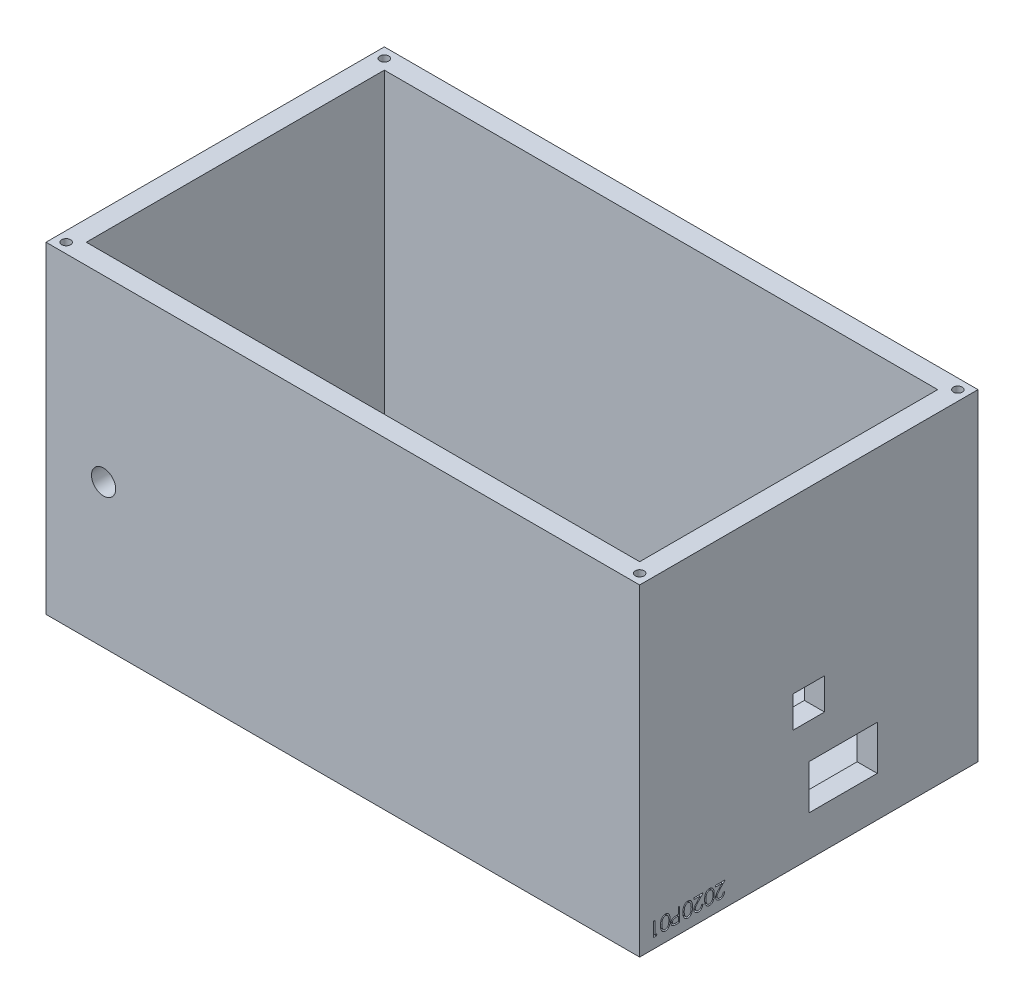
SolidWorks part; units mm, degrees
ref_plane "Front Plane" through (0, 0, 0) normal (0, 0, 1) x (1, 0, 0)
ref_plane "Top Plane" through (0, 0, 0) normal (0, 1, 0) x (1, 0, 0)
ref_plane "Right Plane" through (0, 0, 0) normal (1, 0, 0) x (0, 0, -1)
sketch "Sketch1" plane through (0, 0, 0) normal (0, 1, 0) x (1, 0, 0)
  line L0 (0, 0) -> (-147.35, 0)
  line L1 (-147.35, 0) -> (-147.35, 83.98)
  line L2 (-147.35, 83.98) -> (0, 83.98)
  line L3 (0, 83.98) -> (0, 0)
  dimension "D1" = 147.35
  dimension "D2" = 83.98
extrude "platform_thickness" add sketch "Sketch1" along normal blind 5
sketch "Sketch2" plane through (0, 5, 0) normal (0, 1, 0) x (1, 0, 0)
  line L0 (-147.35, 83.98) -> (-147.35, 0)
  line L1 (-147.35, 0) -> (0, 0)
  line L2 (0, 0) -> (0, 83.98)
  line L3 (0, 83.98) -> (-147.35, 83.98)
  line L4 (-142.35, 78.98) -> (-142.35, 5)
  line L5 (-142.35, 5) -> (-5, 5)
  line L6 (-5, 5) -> (-5, 78.98)
  line L7 (-5, 78.98) -> (-142.35, 78.98)
  line L8 (-5, 5) -> (-5, 0) construction
  line L9 (-5, 5) -> (0, 5) construction
  line L10 (-142.35, 5) -> (-147.35, 5) construction
  line L11 (-142.35, 78.98) -> (-142.35, 83.98) construction
  dimension "D1" = 5
  dimension "D2" = 5
extrude "side_thickness" add sketch "Sketch2" along normal blind 75
sketch "Sketch5" plane through (0, 80, 0) normal (0, 1, 0) x (1, 0, 0)
  line L0 (-2.5, 2.5) -> (-2.5, 81.48) construction
  line L1 (-2.5, 81.48) -> (-144.85, 81.48) construction
  line L2 (-144.85, 81.48) -> (-144.85, 2.5) construction
  line L3 (-144.85, 2.5) -> (-2.5, 2.5) construction
  line L4 (-144.85, 2.5) -> (-144.85, 0) construction
  line L5 (-147.35, 0) -> (0, 0) construction
  line L6 (-144.85, 81.48) -> (-144.85, 83.98) construction
  line L7 (0, 83.98) -> (-147.35, 83.98) construction
  line L8 (-2.5, 2.5) -> (-2.5, 0) construction
  line L9 (-2.5, 81.48) -> (-2.5, 83.98) construction
  line L10 (-144.85, 2.5) -> (-147.35, 2.5) construction
  line L11 (-147.35, 83.98) -> (-147.35, 0) construction
  line L12 (-144.85, 81.48) -> (-147.35, 81.48) construction
  line L13 (-2.5, 81.48) -> (0, 81.48) construction
  line L14 (0, 0) -> (0, 83.98) construction
  line L15 (-2.5, 2.5) -> (0, 2.5) construction
  circle A0 centre (-144.85, 2.5) radius 1.1
  circle A1 centre (-144.85, 81.48) radius 1.1
  circle A2 centre (-2.5, 81.48) radius 1.1
  circle A3 centre (-2.5, 2.5) radius 1.1
  dimension "D1" = 2.2
  dimension "D2" = 2.5
extrude "mounting_holes_1" cut sketch "Sketch5" against normal blind 5
sketch "Sketch11" plane through (0, 0, 0) normal (0, 0, 1) x (1, 0, 0)
  line L0 (-147.35, 0) -> (0, 0) construction
  line L1 (-147.35, 80) -> (-147.35, 0) construction
  circle A0 centre (-133.06, 35.59) radius 3
  point P6 (-147.35, 35.1186)
  point P9 (-126.9793, 33.4193)
  dimension "D1" = 6
  dimension "D2" = 35.59
  dimension "D3" = 14.29
extrude "io_hole_3" cut sketch "Sketch11" against normal blind 50
sketch "Sketch6" plane through (0, 0, 0) normal (1, 0, 0) x (0, 0, -1)
  line L0 (38.09, 37.54) -> (45.89, 37.54)
  line L1 (45.89, 37.54) -> (45.89, 29.74)
  line L2 (45.89, 29.74) -> (38.09, 29.74)
  line L3 (38.09, 29.74) -> (38.09, 37.54)
  line L4 (45.89, 37.54) -> (83.98, 37.54) construction
  line L5 (83.98, 80) -> (83.98, 0) construction
  line L6 (38.09, 37.54) -> (0, 37.54) construction
  line L7 (0, 80) -> (0, 0) construction
  line L8 (38.09, 29.74) -> (38.09, 0) construction
  line L9 (0, 0) -> (83.98, 0) construction
  dimension "D1" = 7.8
  dimension "D3" = 7.8
  dimension "D4" = 29.74
extrude "io_hole_1" cut sketch "Sketch6" against normal blind 92
sketch "Sketch10" plane through (0, 0, 0) normal (1, 0, 0) x (0, 0, -1)
  line L0 (41.98, 21) -> (58.98, 21)
  line L1 (58.98, 21) -> (58.98, 10)
  line L2 (58.98, 10) -> (41.98, 10)
  line L3 (41.98, 10) -> (41.98, 21)
  line L4 (83.98, 80) -> (83.98, 0) construction
  line L5 (0, 0) -> (83.98, 0) construction
  dimension "D1" = 17
  dimension "D2" = 11
  dimension "D3" = 25
  dimension "D4" = 10
extrude "io_hole_2" cut sketch "Sketch10" against normal blind 80
sketch "Sketch9" plane through (0, 0, 0) normal (1, 0, 0) x (0, 0, -1)
  line L0 (0, 80) -> (0, 0) construction
  line L2 (0, 0) -> (83.98, 0) construction
  text T0 "<r180>10P0202</r>"
  dimension "D1" = 6
  dimension "D2" = 5
extrude "text_1" cut sketch "Sketch9" against normal blind 1
